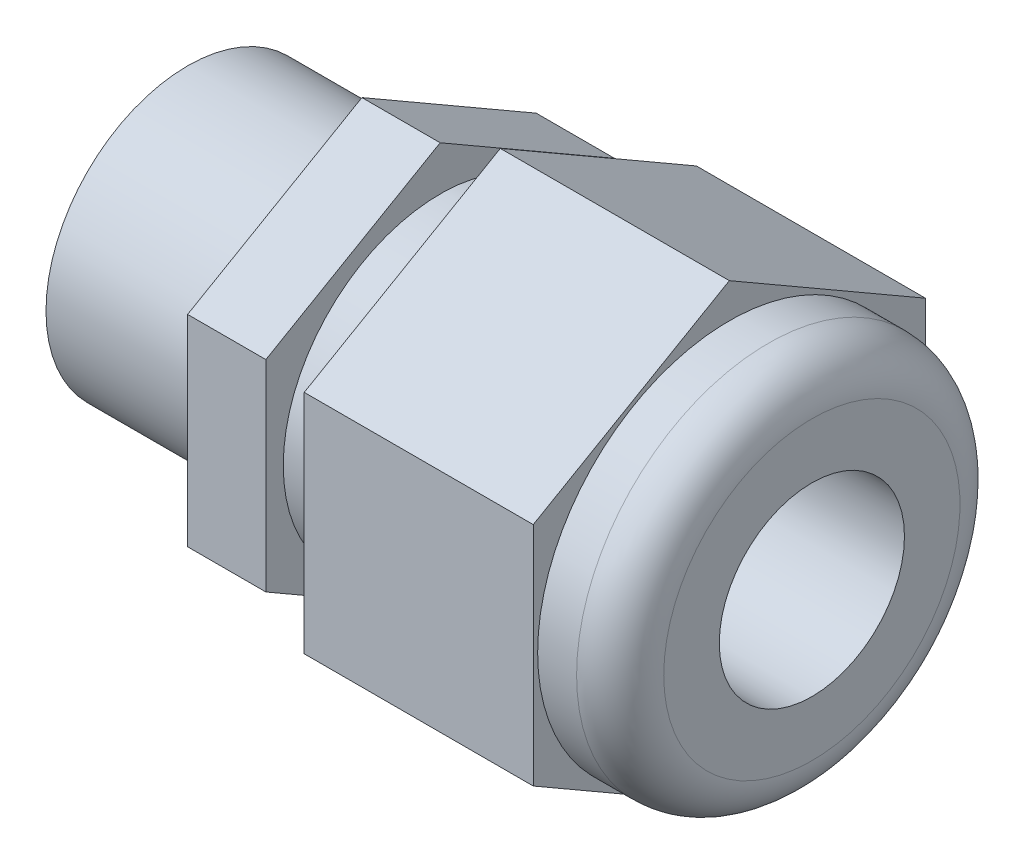
SolidWorks part; units mm, degrees
ref_plane "Přední rovina" through (0, 0, 0) normal (0, 0, 1) x (1, 0, 0)
ref_plane "Horní rovina" through (0, 0, 0) normal (0, 1, 0) x (1, 0, 0)
ref_plane "Pravá rovina" through (0, 0, 0) normal (1, 0, 0) x (0, 0, -1)
sketch "Sketch1" plane through (0, 0, 0) normal (0, 0, 1) x (1, 0, 0)
  line L0 (0, 0) -> (18.0824, 0) construction
  line L1 (0, 4.25) -> (28.6525, 4.25)
  line L2 (28.6525, 4.25) -> (28.6525, 8.7987)
  line L3 (28.6525, 8.7987) -> (24.8644, 8.7987)
  line L4 (24.8644, 8.7987) -> (24.8644, 11)
  line L5 (24.8644, 11) -> (14.3525, 11)
  line L6 (14.3525, 11) -> (14.3525, 7.2022)
  line L7 (14.3525, 7.2022) -> (11.5918, 7.2022)
  line L8 (11.5918, 7.2022) -> (11.5918, 10)
  line L9 (11.5918, 10) -> (8, 10)
  line L10 (8, 10) -> (8, 6.5)
  line L11 (8, 6.5) -> (0, 6.5)
  line L12 (0, 6.5) -> (0, 4.25)
  dimension "D1" = 8.5
  dimension "D2" = 13
  dimension "D3" = 8
  dimension "D5" = 14.3
  dimension "D6" = 20
  dimension "D7" = 22
revolve "Revolve1" add sketch "Sketch1" angle 360 about L0
sketch "Sketch2" plane through (24.8644, 0, 0) normal (1, 0, 0) x (0, 0, -1)
  line L1 (0, 10.3923) -> (-9, 5.1962)
  line L2 (-9, 5.1962) -> (-9, -5.1962)
  line L3 (-9, -5.1962) -> (0, -10.3923)
  line L4 (0, -10.3923) -> (9, -5.1962)
  line L5 (9, -5.1962) -> (9, 5.1962)
  line L6 (9, 5.1962) -> (0, 10.3923)
  circle A0 centre (0, 0) radius 9 construction
  circle A1 centre (0, 0) radius 15.7165
  dimension "D1" = 18
extrude "Cut-Extrude2" cut sketch "Sketch2" against normal blind 12
sketch "Sketch3" plane through (8, 0, 0) normal (-1, 0, 0) x (0, 0, 1)
  line L1 (0, 9.2376) -> (-8, 4.6188)
  line L2 (-8, 4.6188) -> (-8, -4.6188)
  line L3 (-8, -4.6188) -> (0, -9.2376)
  line L4 (0, -9.2376) -> (8, -4.6188)
  line L5 (8, -4.6188) -> (8, 4.6188)
  line L6 (8, 4.6188) -> (0, 9.2376)
  circle A0 centre (0, 0) radius 8 construction
  circle A1 centre (0, 0) radius 15.6434
  dimension "D1" = 16
extrude "Cut-Extrude3" cut sketch "Sketch3" against normal blind 5
fillet "Fillet1" radius 2 1 edges at (28.6525, 0, 8.7987)
